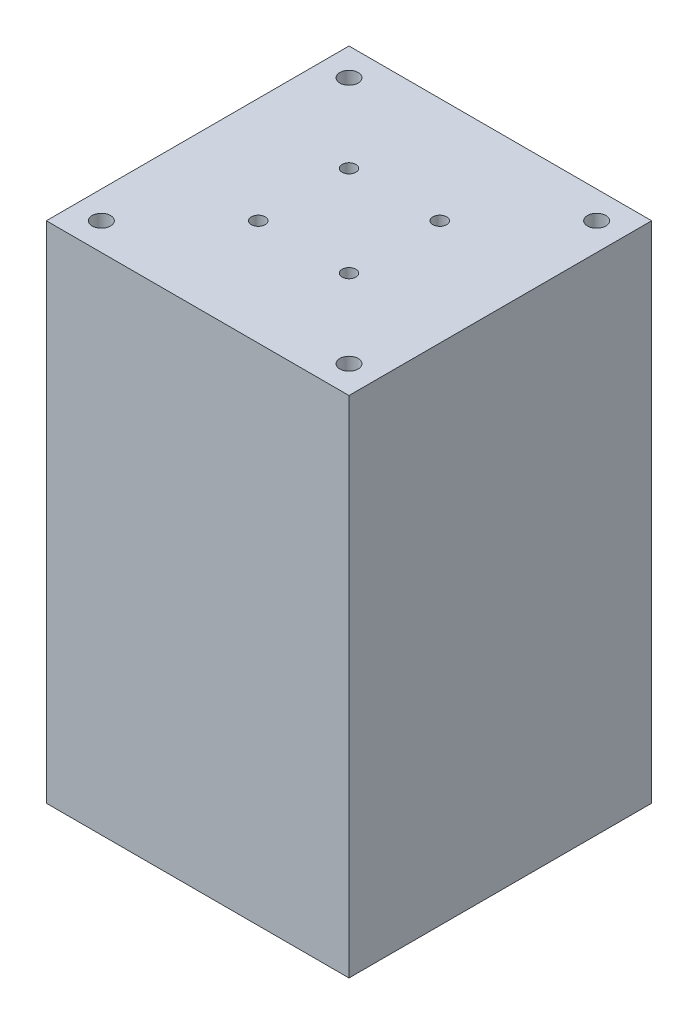
SolidWorks part; units mm, degrees
ref_plane "前视基准面" through (0, 0, 0) normal (0, 0, 1) x (1, 0, 0)
ref_plane "上视基准面" through (0, 0, 0) normal (0, 1, 0) x (1, 0, 0)
ref_plane "右视基准面" through (0, 0, 0) normal (1, 0, 0) x (0, 0, -1)
sketch "草图1" plane through (0, 0, 0) normal (0, 1, 0) x (1, 0, 0)
  line L1 (-21, 21) -> (21, 21)
  line L2 (-21, 21) -> (-21, -21)
  line L3 (-21, -21) -> (21, -21)
  line L4 (21, 21) -> (21, -21)
  line L5 (-21, 21) -> (21, -21) construction
  line L6 (-21, -21) -> (21, 21) construction
  line L7 (-33, 33) -> (33, 33)
  line L8 (-33, 33) -> (-33, -33)
  line L9 (-33, -33) -> (33, -33)
  line L10 (33, 33) -> (33, -33)
  line L11 (-33, 33) -> (33, -33) construction
  line L12 (-33, -33) -> (33, 33) construction
  point P0 (0, 0)
  point P6 (0, 0)
  dimension "D1" = 42
  dimension "D2" = 66
extrude "凸台-拉伸1" add sketch "草图1" along normal blind 110 contours L10 L7 L8 L9 L1 L4 L3 L2 | L4 L1 L2 L3
sketch "草图2" plane through (0, 0, 0) normal (0, -1, 0) x (1, 0, 0)
  line L1 (-21, 21) -> (21, 21)
  line L2 (-21, 21) -> (-21, -21)
  line L3 (-21, -21) -> (21, -21)
  line L4 (-33, -33) -> (33, -33)
  line L5 (33, -33) -> (33, 33)
  line L6 (33, 33) -> (-33, 33)
  line L7 (-33, 33) -> (-33, -33)
  line L8 (-33, -33) -> (33, -33)
  line L9 (33, -33) -> (33, 33)
  line L10 (33, 33) -> (-33, 33)
  line L11 (-33, 33) -> (-33, -33)
  line L12 (-21, -21) -> (21, -21)
  line L13 (21, -21) -> (21, 21)
  line L14 (21, 21) -> (-21, 21)
  line L15 (-21, 21) -> (-21, -21)
  line L16 (-21, -21) -> (21, -21)
  line L17 (21, -21) -> (21, 21)
  line L18 (21, 21) -> (-21, 21)
  line L19 (-21, 21) -> (-21, -21)
  line L20 (21, 21) -> (21, -21)
  line L21 (-21, 21) -> (21, -21) construction
  line L22 (-21, -21) -> (21, 21) construction
  point P6 (0, 0)
  dimension "D1" = 0
  dimension "D2" = 0
extrude "切除-拉伸1" cut sketch "草图2" against normal blind 76 contours L3 L17 L1 L2
sketch "草图3" plane through (0, 76, 0) normal (0, -1, 0) x (1, 0, 0)
  circle A0 centre (0, 0) radius 18
  dimension "D1" = 36
extrude "切除-拉伸2" cut sketch "草图3" against normal blind 28 contours A0
sketch "草图4" plane through (0, 104, 0) normal (0, -1, 0) x (1, 0, 0)
  circle A0 centre (0, 0) radius 11
  dimension "D1" = 22
extrude "切除-拉伸3" cut sketch "草图4" against normal blind 2
sketch "草图5" plane through (0, 110, 0) normal (0, 1, 0) x (1, 0, 0)
  line L1 (-27, 27) -> (27, 27)
  line L2 (-27, 27) -> (-27, -27)
  line L3 (-27, -27) -> (27, -27)
  line L4 (27, 27) -> (27, -27)
  line L5 (-27, 27) -> (27, -27) construction
  line L6 (-27, -27) -> (27, 27) construction
  circle A0 centre (0, 0) radius 14
  circle A1 centre (-9.8995, 9.8995) radius 1.5
  circle A2 centre (9.8995, 9.8995) radius 1.5
  circle A3 centre (9.8995, -9.8995) radius 1.5
  circle A4 centre (-9.8995, -9.8995) radius 1.5
  circle A5 centre (-27, 27) radius 2
  circle A6 centre (27, 27) radius 2
  circle A7 centre (-27, -27) radius 2
  circle A8 centre (27, -27) radius 2
  dimension "D1" = 28
  dimension "D3" = 3
  dimension "D4" = 4
  dimension "D2" = 54
extrude "切除-拉伸4" cut sketch "草图5" against normal through all contours A4 | A1 | A2 | A3 | A5 | A6 | A7 | A8
chamfer "倒角1" distance 6 angle 45 4 edges at (21, 38, 21) (-21, 38, 21) (21, 38, -21) (-21, 38, -21)
sketch "草图6" plane through (0, 0, -33) normal (0, 0, -1) x (-1, 0, 0)
  line L0 (33, 0) -> (-33, 0) construction
  line L1 (-8, 25) -> (8, 25)
  line L2 (-8, 25) -> (-8, 0)
  line L3 (-8, 0) -> (8, 0)
  line L4 (8, 25) -> (8, 0)
  line L5 (-8, 25) -> (8, 0) construction
  line L6 (-8, 0) -> (8, 25) construction
  point P0 (0, 12.5)
  point P5 (0, 0)
  dimension "D1" = 25
  dimension "D2" = 16
extrude "切除-拉伸5" cut sketch "草图6" against normal up to next
sketch "草图7" plane through (-33, 0, 0) normal (-1, 0, 0) x (0, 0, 1)
  line L0 (-33, 0) -> (33, 0) construction
  line L1 (-12.5, 10) -> (12.5, 10)
  line L2 (-12.5, 10) -> (-12.5, 0)
  line L3 (-12.5, 0) -> (12.5, 0)
  line L4 (12.5, 10) -> (12.5, 0)
  line L5 (-12.5, 10) -> (12.5, 0) construction
  line L6 (-12.5, 0) -> (12.5, 10) construction
  point P0 (0, 5)
  point P5 (0, 0)
  dimension "D1" = 10
  dimension "D2" = 25
extrude "切除-拉伸6" cut sketch "草图7" against normal up to next
